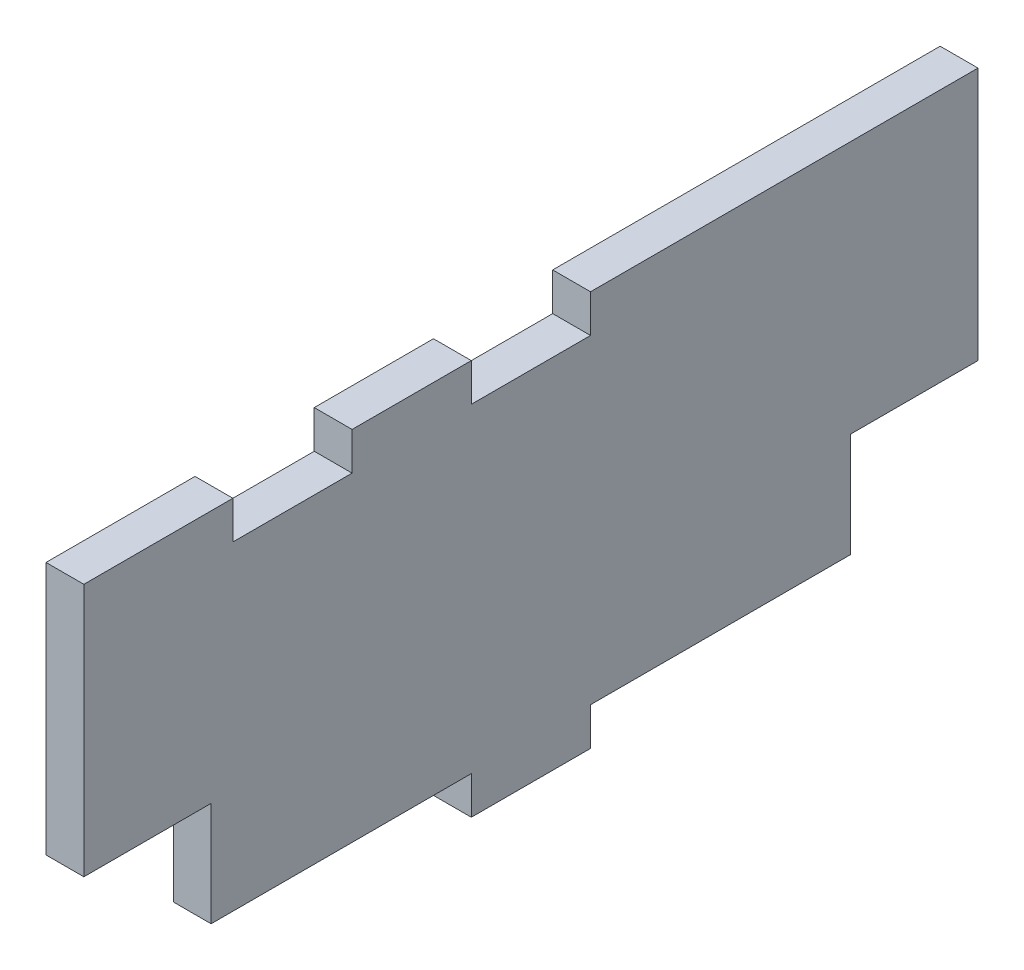
SolidWorks part; units mm, degrees
ref_plane "Front Plane" through (0, 0, 0) normal (0, 0, 1) x (1, 0, 0)
ref_plane "Top Plane" through (0, 0, 0) normal (0, 1, 0) x (1, 0, 0)
ref_plane "Right Plane" through (0, 0, 0) normal (1, 0, 0) x (0, 0, -1)
sketch "Sketch1" plane through (0, 0, 0) normal (1, 0, 0) x (0, 0, -1)
  line L0 (0, 0) -> (0, -60) construction
  line L1 (-150, 60) -> (150, 60)
  line L2 (-150, 60) -> (-150, -60)
  line L3 (-150, -60) -> (150, -60)
  line L4 (150, 60) -> (150, -60)
  line L5 (0, 0) -> (150, 0) construction
  line L7 (-20, -60) -> (20, -60)
  line L8 (-20, -60) -> (-20, -72.7)
  line L9 (-20, -72.7) -> (20, -72.7)
  line L10 (20, -60) -> (20, -72.7)
  point P9 (20, -66.35)
  dimension "D1" = 300
  dimension "D2" = 120
  dimension "D3" = 12.7
  dimension "D4" = 40
  dimension "D5" = 130
extrude "Boss-Extrude1" add sketch "Sketch1" along normal blind 12.7 contours L1 L4 L3 L2 | L9 L10 L7 L8
sketch "Sketch2" plane through (12.7, 0, 0) normal (1, 0, 0) x (0, 0, -1)
  line L0 (-150, 60) -> (-150, -60) construction
  line L1 (-150, -25) -> (-107.3, -25)
  line L2 (-150, -25) -> (-150, -60)
  line L3 (-150, -60) -> (-107.3, -60)
  line L4 (-107.3, -25) -> (-107.3, -60)
  line L5 (-150, -60) -> (-20, -60) construction
  line L6 (150, 60) -> (150, -60) construction
  line L7 (150, -25) -> (107.3, -25)
  line L8 (150, -25) -> (150, -60)
  line L9 (150, -60) -> (107.3, -60)
  line L10 (107.3, -25) -> (107.3, -60)
  line L11 (20, -60) -> (150, -60) construction
  dimension "D1" = 35
  dimension "D2" = 42.7
extrude "Cut-Extrude1" cut sketch "Sketch2" against normal blind 12.7
sketch "Sketch3" plane through (12.7, 0, 0) normal (1, 0, 0) x (0, 0, -1)
  line L0 (-150, 60) -> (150, 60) construction
  line L1 (-20, 60) -> (20, 60)
  line L2 (-20, 60) -> (-20, 47.3)
  line L3 (-20, 47.3) -> (20, 47.3)
  line L4 (20, 60) -> (20, 47.3)
  line L5 (20, -60) -> (20, -72.7) construction
  line L6 (-20, -60) -> (-20, -72.7) construction
  dimension "D1" = 12.7
extrude "Cut-Extrude2" cut sketch "Sketch3" against normal blind 12.7
sketch "Sketch4" plane through (12.7, 0, 0) normal (1, 0, 0) x (0, 0, -1)
  line L0 (-150, 60) -> (-20, 60) construction
  line L1 (-100, 60) -> (-60, 60)
  line L2 (-100, 60) -> (-100, 47.3)
  line L3 (-100, 47.3) -> (-60, 47.3)
  line L4 (-60, 60) -> (-60, 47.3)
  line L5 (-20, 60) -> (-20, 47.3) construction
  dimension "D1" = 12.7
  dimension "D2" = 40
  dimension "D3" = 40
extrude "Cut-Extrude3" cut sketch "Sketch4" against normal blind 12.7
